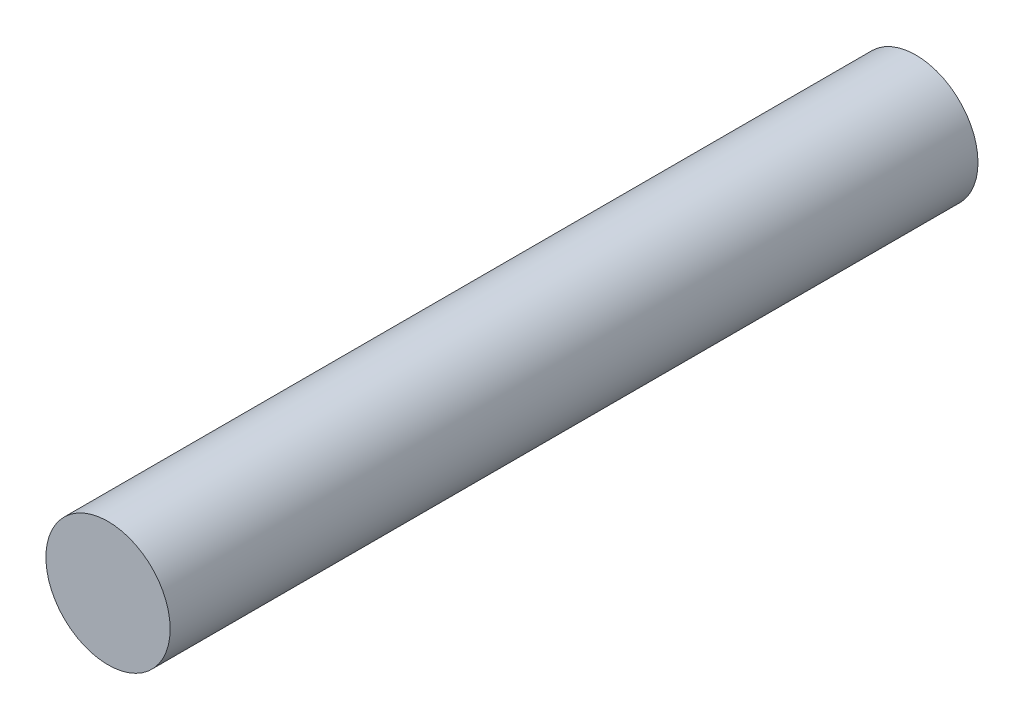
SolidWorks part; units mm, degrees
ref_plane "Front Plane" through (0, 0, 0) normal (0, 0, 1) x (1, 0, 0)
ref_plane "Top Plane" through (0, 0, 0) normal (0, 1, 0) x (1, 0, 0)
ref_plane "Right Plane" through (0, 0, 0) normal (1, 0, 0) x (0, 0, -1)
sketch "Sketch1" plane through (0, 0, 0) normal (0, 0, 1) x (1, 0, 0)
  circle A0 centre (0, 0) radius 6.35
  dimension "D1" = 12.7
extrude "Boss-Extrude1" add sketch "Sketch1" along normal blind 82.55
